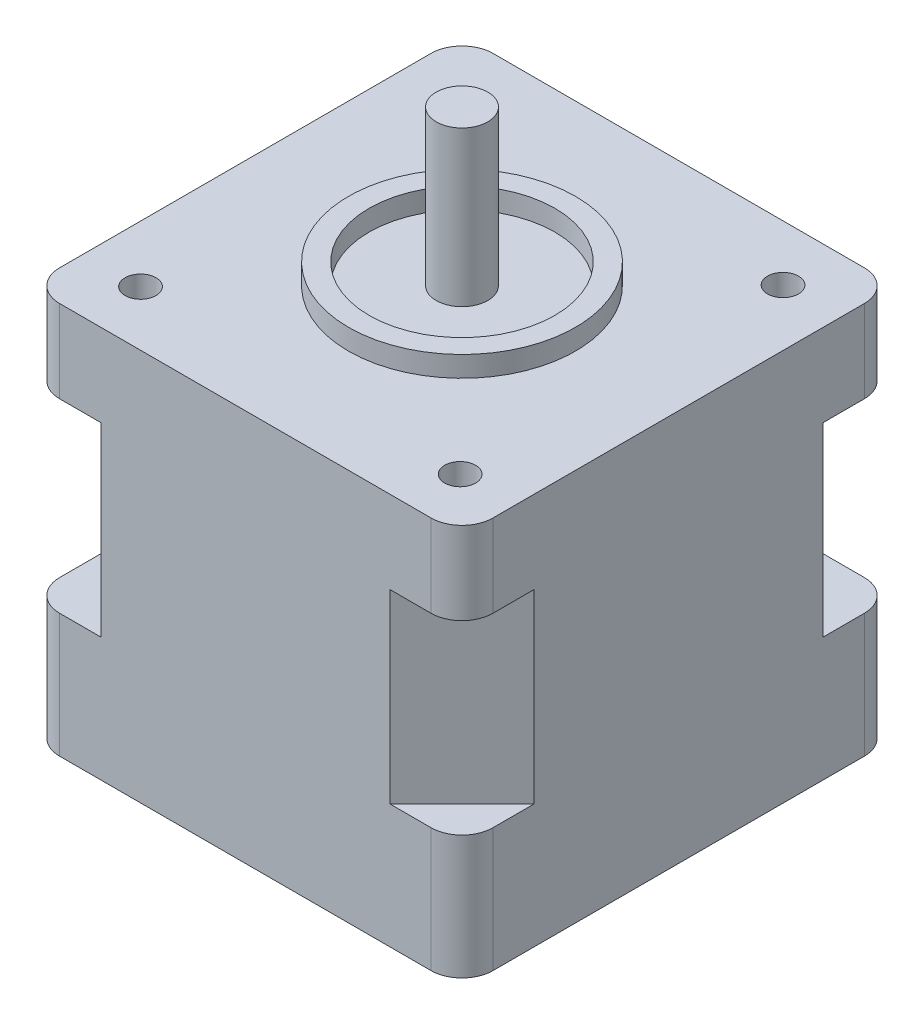
SolidWorks part; units mm, degrees
ref_plane "Front Plane" through (0, 0, 0) normal (0, 0, 1) x (1, 0, 0)
ref_plane "Top Plane" through (0, 0, 0) normal (0, 1, 0) x (1, 0, 0)
ref_plane "Right Plane" through (0, 0, 0) normal (1, 0, 0) x (0, 0, -1)
sketch "Sketch2" plane through (0, 0, 0) normal (0, 1, 0) x (1, 0, 0)
  line L1 (-18, 21) -> (18, 21)
  line L2 (-21, 18) -> (-21, -18)
  line L3 (-18, -21) -> (18, -21)
  line L4 (21, 18) -> (21, -18)
  line L5 (-21, 21) -> (21, -21) construction
  line L6 (-21, -21) -> (21, 21) construction
  arc A0 (-18, -21) -> (-21, -18) centre (-18, -18) cw
  arc A1 (18, -21) -> (21, -18) centre (18, -18) ccw
  arc A2 (18, 21) -> (21, 18) centre (18, 18) cw
  arc A3 (-21, 18) -> (-18, 21) centre (-18, 18) cw
  point P0 (0, 0)
  dimension "D3" = 3
  dimension "D1" = 42
  dimension "D2" = 42
extrude "Boss-Extrude1" add sketch "Sketch2" along normal blind 12
sketch "Sketch3" plane through (0, 12, 0) normal (0, 1, 0) x (1, 0, 0)
  line L0 (-21, 14) -> (-14, 21)
  line L1 (-14, 21) -> (14, 21)
  line L2 (-21, 14) -> (-21, -14)
  line L3 (-14, -21) -> (14, -21)
  line L4 (21, 14) -> (21, -14)
  line L5 (-21, 21) -> (21, -21) construction
  line L6 (-21, -21) -> (21, 21) construction
  line L7 (14, 21) -> (21, 14)
  line L8 (21, -14) -> (14, -21)
  line L9 (-21, -14) -> (-14, -21)
  point P0 (0, 0)
extrude "Boss-Extrude2" add sketch "Sketch3" along normal blind 18
sketch "Sketch4" plane through (0, 30, 0) normal (0, 1, 0) x (1, 0, 0)
  line L1 (-18, 21) -> (18, 21)
  line L2 (-21, 18) -> (-21, -18)
  line L3 (-18, -21) -> (18, -21)
  line L4 (21, 18) -> (21, -18)
  line L5 (-21, 21) -> (21, -21) construction
  line L6 (-21, -21) -> (21, 21) construction
  arc A0 (21, 18) -> (18, 21) centre (18, 18) ccw
  arc A1 (18, -21) -> (21, -18) centre (18, -18) ccw
  arc A2 (-18, -21) -> (-21, -18) centre (-18, -18) cw
  arc A3 (-21, 18) -> (-18, 21) centre (-18, 18) cw
  point P0 (0, 0)
  dimension "D3" = 3
  dimension "D1" = 42
  dimension "D2" = 42
extrude "Boss-Extrude3" add sketch "Sketch4" along normal blind 8
sketch "Sketch5" plane through (0, 38, 0) normal (0, 1, 0) x (1, 0, 0)
  circle A0 centre (0, 0) radius 11
  circle A1 centre (0, 0) radius 9
  dimension "D1" = 22
  dimension "D2" = 18
extrude "Boss-Extrude4" add sketch "Sketch5" along normal blind 2
sketch "Sketch6" plane through (0, 38, 0) normal (0, 1, 0) x (1, 0, 0)
  circle A0 centre (0, 0) radius 2.5
  dimension "D1" = 5
extrude "Boss-Extrude5" add sketch "Sketch6" along normal blind 15
sketch "Sketch7" plane through (0, 38, 0) normal (0, 1, 0) x (1, 0, 0)
  line L1 (-15.5, -15.5) -> (15.5, -15.5) construction
  line L2 (-15.5, -15.5) -> (-15.5, 15.5) construction
  line L3 (-15.5, 15.5) -> (15.5, 15.5) construction
  line L4 (15.5, -15.5) -> (15.5, 15.5) construction
  line L5 (-15.5, -15.5) -> (15.5, 15.5) construction
  line L6 (-15.5, 15.5) -> (15.5, -15.5) construction
  circle A0 centre (-15.5, 15.5) radius 1.5
  circle A1 centre (15.5056, 15.6114) radius 1.5
  circle A2 centre (15.7326, -15.9129) radius 1.5
  circle A3 centre (-15.4949, -15.6632) radius 1.5
  point P0 (0, 0)
  dimension "D3" = 3
  dimension "D1" = 31
  dimension "D2" = 31
extrude "Cut-Extrude1" cut sketch "Sketch7" against normal blind 4.5
sketch "Sketch9" plane through (0, 0, -21) normal (0, 0, -1) x (-1, 0, 0)
  line L1 (-7.5, 12) -> (7.5, 12)
  line L2 (-7.5, 12) -> (-7.5, 7)
  line L3 (-7.5, 7) -> (7.5, 7)
  line L4 (7.5, 12) -> (7.5, 7)
  line L5 (-7.5, 12) -> (7.5, 7) construction
  line L6 (-7.5, 7) -> (7.5, 12) construction
  line L7 (14, 12) -> (18, 12) construction
  line L8 (-18, 0) -> (18, 0) construction
  point P0 (0, 9.5)
  point P10 (0, 0)
  dimension "D1" = 15
  dimension "D2" = 5
extrude "Boss-Extrude6" add sketch "Sketch9" along normal blind 5
